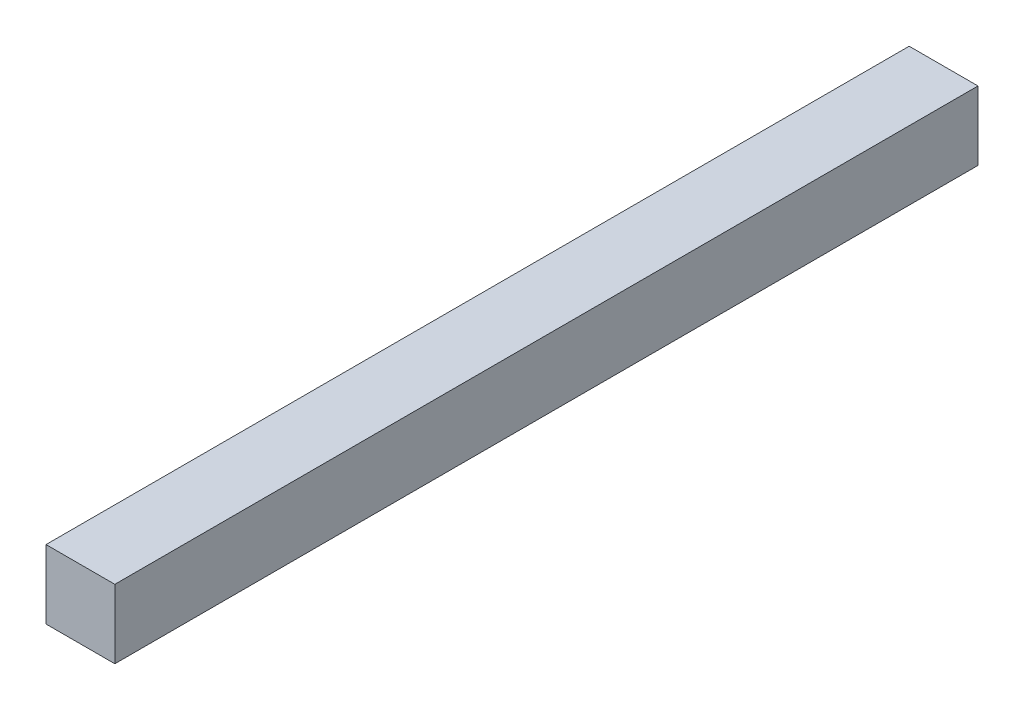
SolidWorks part; units mm, degrees
ref_plane "Front Plane" through (0, 0, 0) normal (0, 0, 1) x (1, 0, 0)
ref_plane "Top Plane" through (0, 0, 0) normal (0, 1, 0) x (1, 0, 0)
ref_plane "Right Plane" through (0, 0, 0) normal (1, 0, 0) x (0, 0, -1)
sketch "Sketch1" plane through (0, 0, 0) normal (0, 0, 1) x (1, 0, 0)
  line L1 (25, 25) -> (-25, 25)
  line L2 (25, 25) -> (25, -25)
  line L3 (25, -25) -> (-25, -25)
  line L4 (-25, 25) -> (-25, -25)
  line L5 (25, 25) -> (-25, -25) construction
  line L6 (25, -25) -> (-25, 25) construction
  point P0 (0, 0)
  dimension "D1" = 50
extrude "Boss-Extrude1" add sketch "Sketch1" along normal blind 627
sketch "Sketch2" plane through (0, 0, 0) normal (0, 0, 1) x (1, 0, 0)
  circle A0 centre (0, 0) radius 5
  dimension "D1" = 10
extrude "Cut-Extrude3" cut sketch "Sketch2" along normal blind 22
